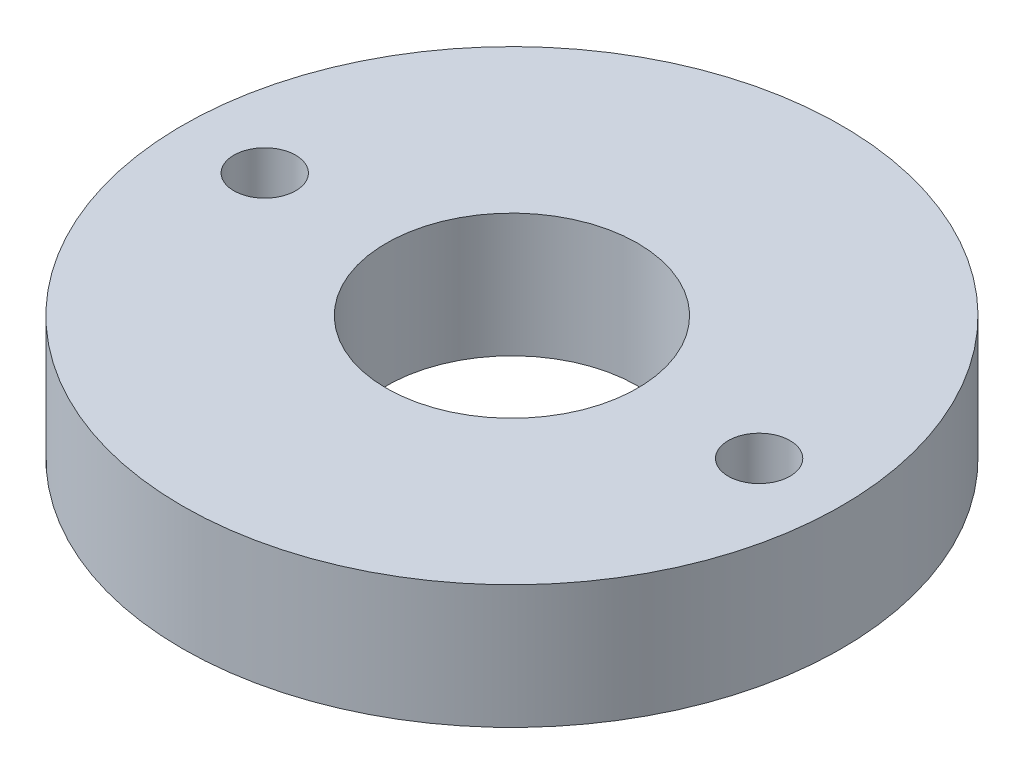
SolidWorks part; units mm, degrees
material "ナイロン"
ref_plane "正面" through (0, 0, 0) normal (0, 0, 1) x (1, 0, 0)
ref_plane "平面" through (0, 0, 0) normal (0, 1, 0) x (1, 0, 0)
ref_plane "右側面" through (0, 0, 0) normal (1, 0, 0) x (0, 0, -1)
sketch "ｽｹｯﾁ1" plane through (0, 0, 0) normal (0, 1, 0) x (1, 0, 0)
  line L0 (0, 0) -> (50000, 0) construction
  line L1 (0, 0) -> (0, 50000) construction
  circle A0 centre (0, 0) radius 16
  circle A1 centre (0, 0) radius 6.1
  circle A2 centre (12, 0) radius 1.5
  circle A3 centre (-12, 0) radius 1.5
  dimension "D1" = 32
  dimension "D2" = 12.2
  dimension "D3" = 24
  dimension "D4" = 3
extrude "ﾎﾞｽ - 押し出し1" add sketch "ｽｹｯﾁ1" along normal blind 6
